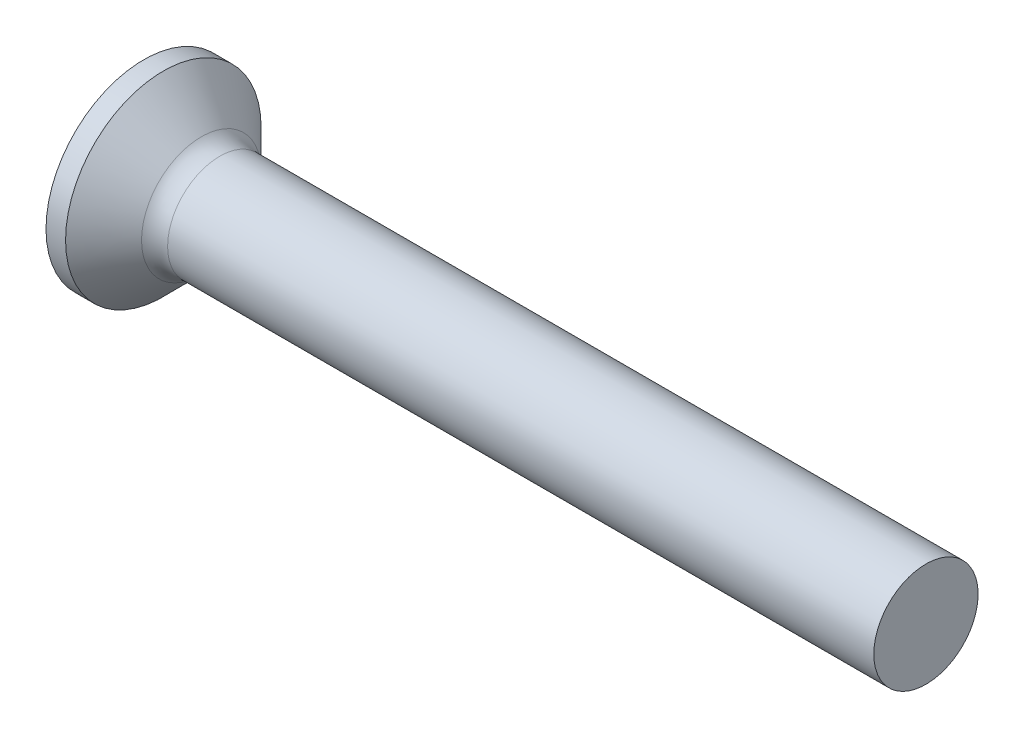
SolidWorks part; units mm, degrees
ref_plane "Plane1" through (0, 0, 0) normal (0, 0, 1) x (1, 0, 0)
ref_plane "Plane2" through (0, 0, 0) normal (0, 1, 0) x (1, 0, 0)
ref_plane "Plane3" through (0, 0, 0) normal (1, 0, 0) x (0, 0, -1)
sketch "BodySke" plane through (0, 0, 0) normal (0, 0, 1) x (1, 0, 0)
  line L0 (0, 0) -> (0, 1.5)
  line L1 (0, 1.5) -> (0.3, 1.5)
  line L2 (1, 0.8) -> (12, 0.8)
  line L3 (12, 0.8) -> (12, 0)
  line L4 (12, 0) -> (0, 0)
  line L5 (-6.35, 0) -> (82.55, 0) construction
  line L6 (1, -0.8) -> (12, -0.8) construction
  line L7 (0.3, -1.5) -> (1, -0.8) construction
  line L8 (0.3, 1.5) -> (1, 0.8)
  line L9 (0, -1.5) -> (0.3, -1.5) construction
  line L10 (1.35, 2.3875) -> (1.35, -7.1375) construction
  line L11 (2, 6.35) -> (2, -3.175) construction
  dimension "Diameter" = 1.6
  dimension "Length" = 12
  dimension "Head_ht" = 1
  dimension "Head_dia" = 3
  dimension "Head_ang" = 90
  dimension "D6" = 0.3
  dimension "Advance" = 0.35
  dimension "Thread_nom" = 10
revolve "Base-Revolve" add sketch "BodySke" angle 360 about L5
cosmetic thread "ThreadCosmetic" [suppressed] parameters "Thread_length"=10, "Thread_minor"=1.202
fillet "Fillet1" radius 0.4 1 edges at (1, 0, 0.8)
sketch "Sketch3" plane through (0, 0, 0) normal (-1, 0, 0) x (0, 0, 1)
  line L0 (-0.24, 0.8) -> (0.24, 0.8)
  line L1 (0.24, 0.8) -> (0.24, -0.8)
  line L2 (0.24, -0.8) -> (-0.24, -0.8)
  line L3 (-0.24, -0.8) -> (-0.24, 0.8)
  dimension "D1" = 0.8
  dimension "Cross_dia" = 1.6
  dimension "D2" = 0.24
  dimension "Cross_width" = 0.48
ref_plane "Plane4" through (0.95, 0, 0) normal (-1, 0, 0) x (0, 0, 1)
sketch "Sketch4" plane through (0.95, 0, 0) normal (-1, 0, 0) x (0, 0, 1)
  line L0 (-0.24, 0.3263) -> (0.24, 0.3263)
  line L3 (0.24, 0.3263) -> (0.24, -0.3263)
  line L4 (0.24, -0.3263) -> (-0.24, -0.3263)
  line L5 (-0.24, -0.3263) -> (-0.24, 0.3263)
  dimension "D1" = 0.48
  dimension "D2" = 0.6527
  dimension "D3" = 0.24
  dimension "D4" = 0.3263
loft "Recess" cut profiles "Sketch3", "Sketch4"
pattern_circular "RecPat" count 2 every 90 about axis through (0, 0, 0) along (1, 0, 0) of "Recess"
sketch "RecCorSke" plane through (0, 0, 0) normal (0, 0, 1) x (1, 0, 0)
  line L0 (-3.175, 0) -> (15.875, 0) construction
  line L2 (0, 0) -> (0, 0.4219)
  line L3 (0, 0.4219) -> (0.95, 0.3555)
  line L4 (0.95, 0.3555) -> (1.0655, 0)
  line L5 (1.0655, 0) -> (0, 0)
  dimension "Diameter" = 0.711
  dimension "Depth" = 0.95
  dimension "Draft_angle" = 4
  dimension "Bottom_angle" = 18
revolve "RecessCore" cut sketch "RecCorSke" angle 360 about L0
sketch "ThdSchSke" plane through (0, 0, 0) normal (0, 0, 1) x (1, 0, 0)
  line L0 (2, -0.601) -> (1.8607, -0.8)
  line L1 (2, -0.601) -> (2.1393, -0.8)
  line L2 (2.1393, -0.8) -> (2.1393, -1)
  line L3 (-3.175, 0) -> (5.1513, 0) construction
  line L5 (2.1393, -1) -> (1.8607, -1)
  line L6 (1.8607, -1) -> (1.8607, -0.8)
  line L7 (0, 1.5) -> (0, -1.5) construction
  dimension "Thread_minor" = 1.202
  dimension "Diameter" = 1.6
  dimension "Start" = 2
  dimension "SideAngle" = 55
  dimension "VeeAngle" = 70
  dimension "Overcut" = 2
revolve "ThreadSchematic" [suppressed] cut sketch "ThdSchSke" angle 360 about L3
pattern_linear "ThdSchPat" [suppressed]
equation "\"D1@Sketch3\" = \"Cross_dia@Sketch3\" / 2"
equation "\"D2@Sketch3\" = \"Cross_width@Sketch3\" / 2"
equation "\"Depth@RecCorSke\" = \"Cross_depth@Plane4\""
equation "\"D1@Sketch4\" = \"Cross_width@Sketch3\""
equation "\"D2@Sketch4\" = \"Cross_dia@Sketch3\" - 2.0 * \"Cross_depth@Plane4\" * tan(26.5  * 0.017453292)"
equation "\"D3@Sketch4\" = \"D1@Sketch4\" / 2"
equation "\"D4@Sketch4\" = \"D2@Sketch4\" / 2"
equation "\"Thread_length@ThreadCosmetic\" = ((sgn( (\"Length@BodySke\" - \"Advance@BodySke\" * 1.0 - \"Head_ht@BodySke\" ) - \"Thread_nom@BodySke\" )-1)*( (\"Length@BodySke\" - \"Advance@BodySke\" * 1.0 - \"Head_ht@BodySke\" ) - \"Thread_nom@BodySke\" ))/-2+ \"Thread_nom@BodySke\""
equation "\"Thread_minor@ThdSchSke\" = \"Thread_minor@ThreadCosmetic\""
equation "\"Diameter@ThdSchSke\" = \"Diameter@BodySke\""
equation "\"Overcut@ThdSchSke\" = \"Diameter@BodySke\" * 1.25"
equation "\"Start@ThdSchSke\" = 0.000001 + \"Length@BodySke\" - \"Thread_length@ThreadCosmetic\"  '---Countersunk---"
equation "\"Num_threads@ThdSchPat\" = int( \"Thread_length@ThreadCosmetic\" / \"Advance@BodySke\" + 0.999 )  + 1"
equation "\"Advance@ThdSchPat\" = \"Thread_length@ThreadCosmetic\" /  (\"Num_threads@ThdSchPat\" - 1) 'relax it"
